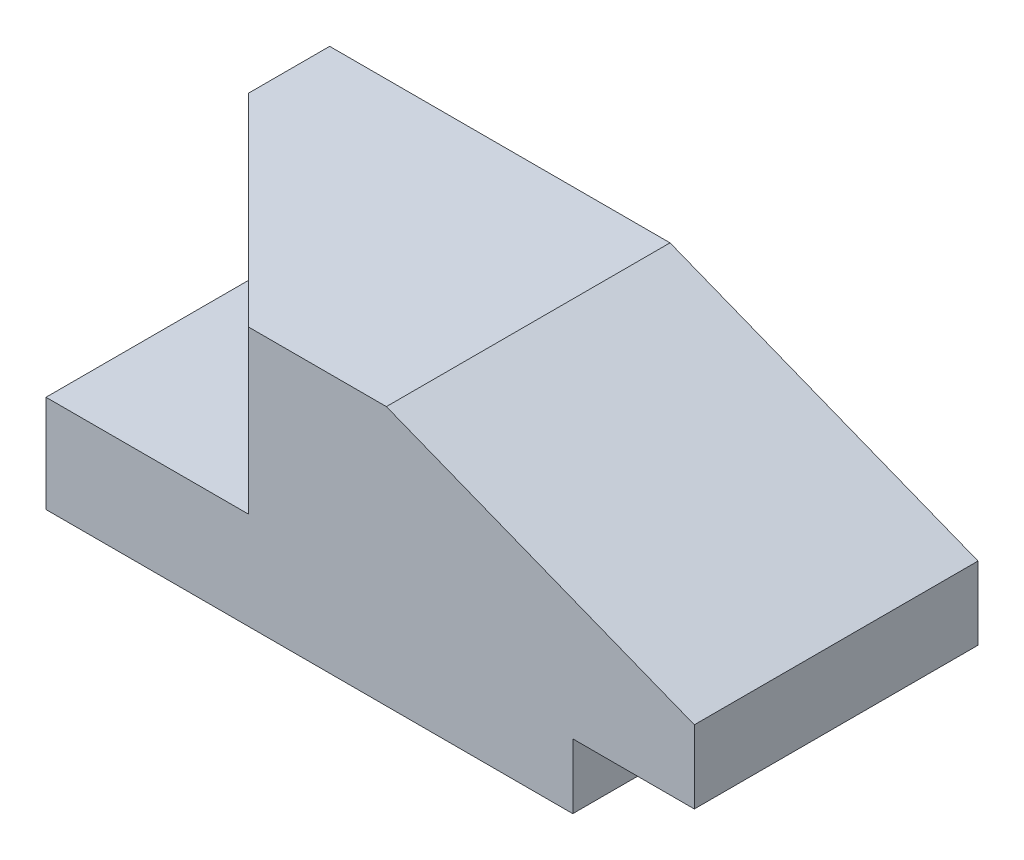
SolidWorks part; units mm, degrees
ref_plane "Front Plane" through (0, 0, 0) normal (0, 0, 1) x (1, 0, 0)
ref_plane "Top Plane" through (0, 0, 0) normal (0, 1, 0) x (1, 0, 0)
ref_plane "Right Plane" through (0, 0, 0) normal (1, 0, 0) x (0, 0, -1)
sketch "Sketch1" plane through (0, 0, 0) normal (0, 0, 1) x (1, 0, 0)
  line L0 (0, 0) -> (0, -8)
  line L1 (0, -8) -> (-65, -8)
  line L2 (-65, -8) -> (-65, 4)
  line L5 (-40, 24) -> (-23, 24)
  line L6 (15, 9) -> (15, 0)
  line L7 (15, 0) -> (0, 0)
  line L8 (15, 9) -> (-23, 24)
  line L9 (-65, 4) -> (-65, 24)
  line L10 (-65, 24) -> (-40, 24)
  dimension "D1" = 65
  dimension "D2" = 15
  dimension "D3" = 8
  dimension "D4" = 12
  dimension "D6" = 15
  dimension "D7" = 42
  dimension "D8" = 32
extrude "Boss-Extrude1" add sketch "Sketch1" against normal blind 35
sketch "Sketch2" plane through (0, 24, 0) normal (0, 1, 0) x (1, 0, 0)
  line L0 (-40, 0) -> (-65, 25)
  line L1 (-23, 0) -> (-65, 0) construction
  line L2 (-65, 35) -> (-65, 0) construction
  line L3 (-65, 25) -> (-65, 0)
  line L4 (-65, 0) -> (-40, 0)
  dimension "D1" = 25
  dimension "D2" = 25
extrude "Cut-Extrude1" cut sketch "Sketch2" against normal blind 20
